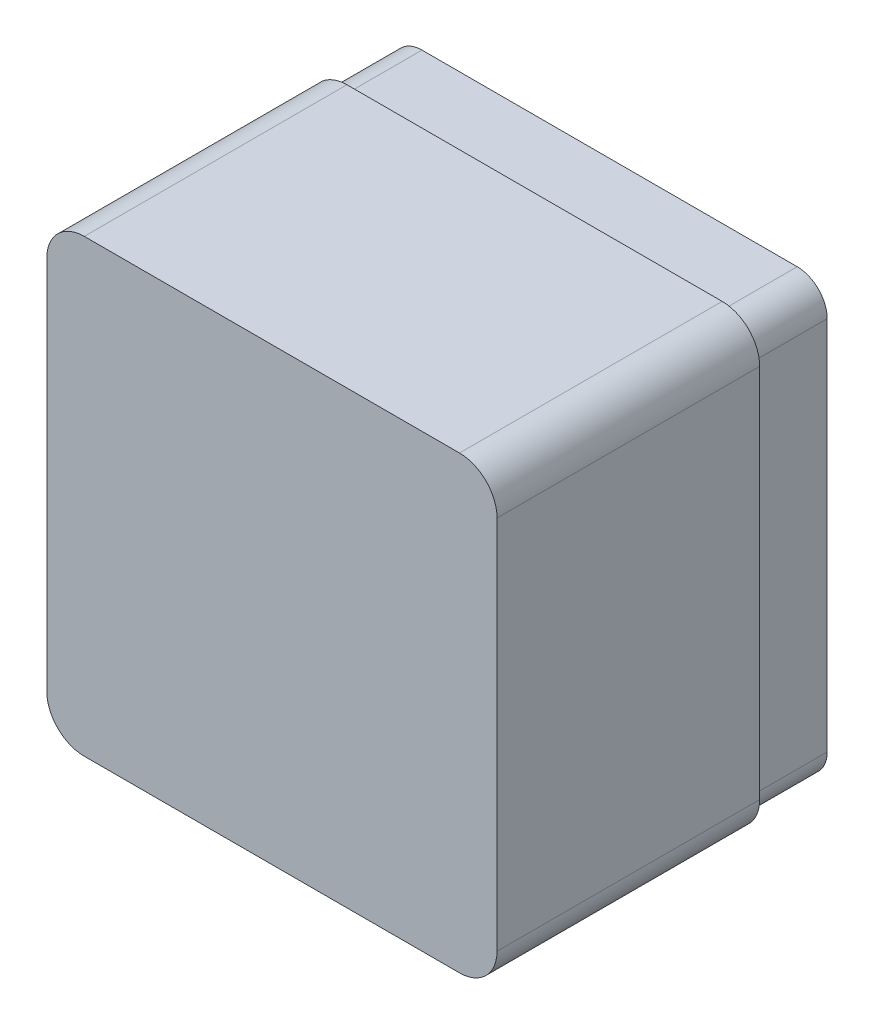
SolidWorks part; units mm, degrees
ref_plane "Front Plane" through (0, 0, 0) normal (0, 0, 1) x (1, 0, 0)
ref_plane "Top Plane" through (0, 0, 0) normal (0, 1, 0) x (1, 0, 0)
ref_plane "Right Plane" through (0, 0, 0) normal (1, 0, 0) x (0, 0, -1)
sketch "Sketch1" plane through (0, 0, 0) normal (0, 0, 1) x (1, 0, 0)
  line L1 (0, 0) -> (120, 0)
  line L2 (0, 0) -> (0, 120)
  line L3 (0, 120) -> (120, 120)
  line L4 (120, 0) -> (120, 120)
  dimension "D1" = 120
  dimension "D2" = 120
extrude "Boss-Extrude1" add sketch "Sketch1" along normal blind 90
fillet "Fillet1" radius 10 4 edges at (120, 0, 45) (120, 120, 45) (0, 0, 45) (0, 120, 45)
shell "Shell1" thickness 4
sketch "Sketch2" plane through (0, 0, 0) normal (0, 0, -1) x (-1, 0, 0)
  line L0 (-118, 110) -> (-118, 10)
  line L1 (-110, 2) -> (-10, 2)
  line L2 (-2, 10) -> (-2, 110)
  line L3 (-10, 118) -> (-110, 118)
  line L4 (-120, 110) -> (-120, 10)
  line L5 (-110, 0) -> (-10, 0)
  line L6 (0, 10) -> (0, 110)
  line L7 (-10, 120) -> (-110, 120)
  line L8 (-120, 110) -> (-120, 10)
  line L9 (-110, 0) -> (-10, 0)
  line L10 (0, 10) -> (0, 110)
  line L11 (-10, 120) -> (-110, 120)
  arc A0 (-118, 10) -> (-110, 2) centre (-110, 10) ccw
  arc A1 (-10, 2) -> (-2, 10) centre (-10, 10) ccw
  arc A2 (-2, 110) -> (-10, 118) centre (-10, 110) ccw
  arc A3 (-110, 118) -> (-118, 110) centre (-110, 110) ccw
  arc A4 (-120, 10) -> (-110, 0) centre (-110, 10) ccw
  arc A5 (-10, 0) -> (0, 10) centre (-10, 10) ccw
  arc A6 (0, 110) -> (-10, 120) centre (-10, 110) ccw
  arc A7 (-110, 120) -> (-120, 110) centre (-110, 110) ccw
  arc A8 (-120, 10) -> (-110, 0) centre (-110, 10) ccw
  arc A9 (-10, 0) -> (0, 10) centre (-10, 10) ccw
  arc A10 (0, 110) -> (-10, 120) centre (-10, 110) ccw
  arc A11 (-110, 120) -> (-120, 110) centre (-110, 110) ccw
  dimension "D1" = 0
  dimension "D2" = 2
extrude "Cut-Extrude1" cut sketch "Sketch2" against normal blind 20
